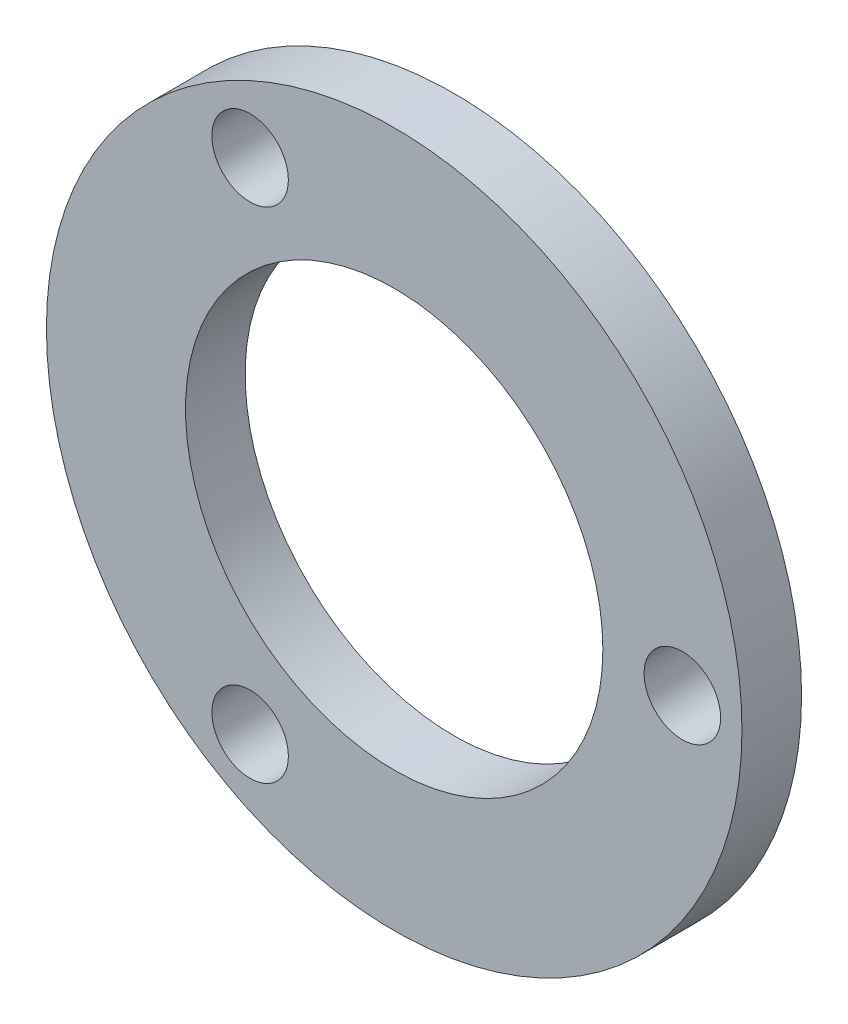
SolidWorks part; units mm, degrees
ref_plane "Plan de face" through (0, 0, 0) normal (0, 0, 1) x (1, 0, 0)
ref_plane "Plan de dessus" through (0, 0, 0) normal (0, 1, 0) x (1, 0, 0)
ref_plane "Plan de droite" through (0, 0, 0) normal (1, 0, 0) x (0, 0, -1)
sketch "Esquisse1" plane through (0, 0, 0) normal (0, 0, 1) x (1, 0, 0)
  line L0 (0.0002, 0) -> (14.5002, 0) construction
  circle A0 centre (0.0002, 0) radius 17.5
  circle A1 centre (-7.2501, -12.5576) radius 1.925
  circle A2 centre (-7.2501, 12.5576) radius 1.925
  circle A3 centre (0.0002, 0) radius 10.5
  circle A12 centre (14.5002, 0) radius 1.925
  point P9 (0, 0)
  dimension "D1" = 21
  dimension "D2" = 3.85
  dimension "D3" = 35
  dimension "D4" = 14.5
  dimension "D5" = 3
extrude "Boss.-Extru.1" add sketch "Esquisse1" along normal blind 3
